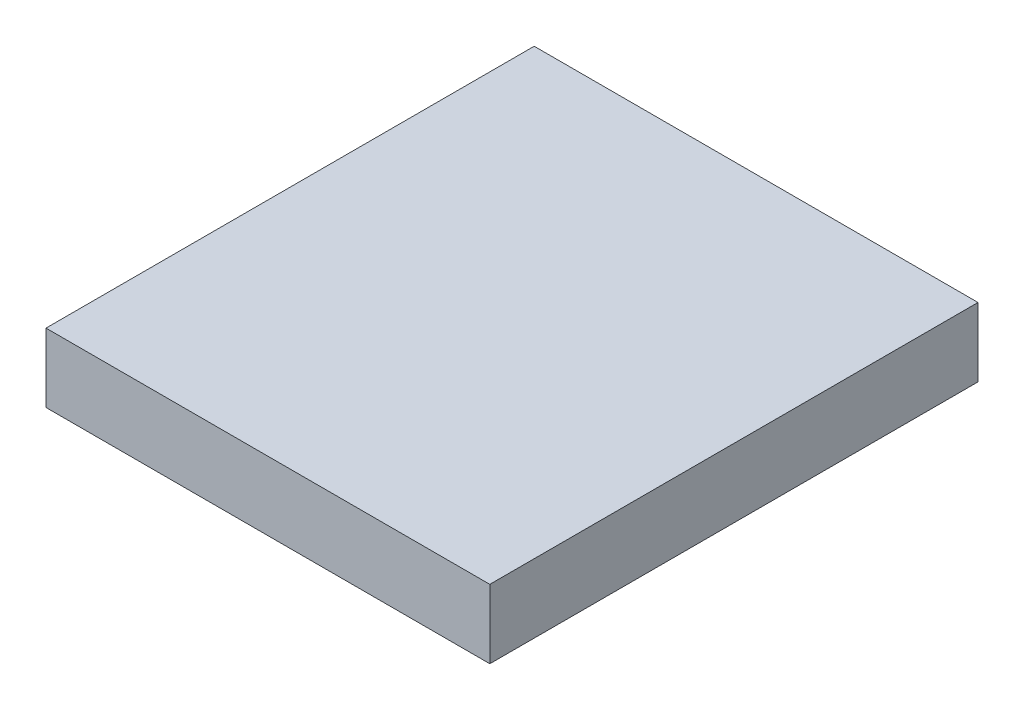
SolidWorks part; units mm, degrees
ref_plane "Front Plane" through (0, 0, 0) normal (0, 0, 1) x (1, 0, 0)
ref_plane "Top Plane" through (0, 0, 0) normal (0, 1, 0) x (1, 0, 0)
ref_plane "Right Plane" through (0, 0, 0) normal (1, 0, 0) x (0, 0, -1)
sketch "Sketch1" plane through (0, 0, 0) normal (0, 1, 0) x (1, 0, 0)
  line L1 (-50, -55) -> (50, -55)
  line L2 (-50, -55) -> (-50, 55)
  line L3 (-50, 55) -> (50, 55)
  line L4 (50, -55) -> (50, 55)
extrude "Gear_pump_riser_blank" add sketch "Sketch1" along normal blind 15.5 from offset 0 separate body
